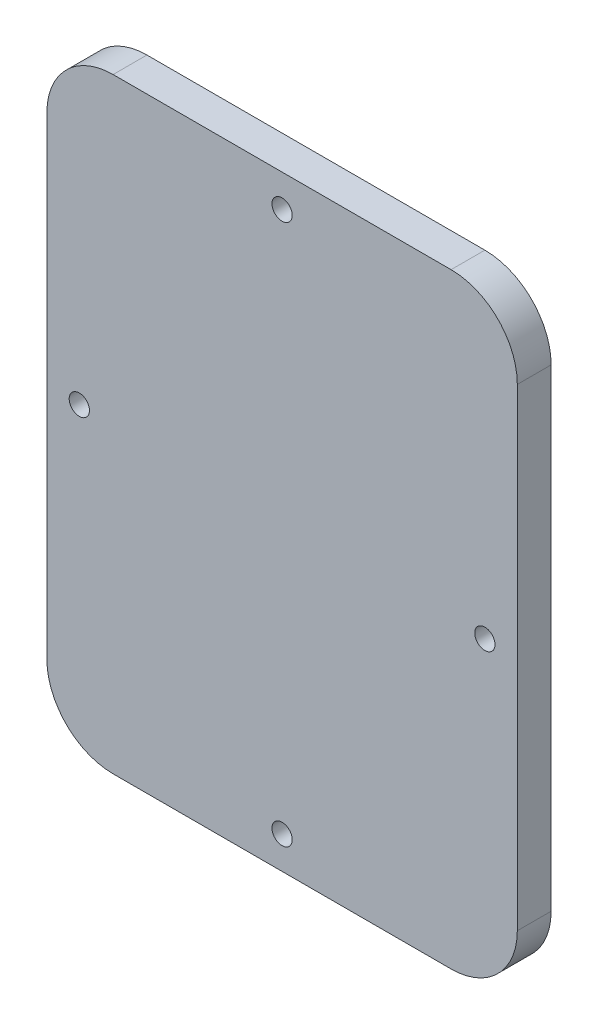
SolidWorks part; units mm, degrees
ref_plane "Plano frontal" through (0, 0, 0) normal (0, 0, 1) x (1, 0, 0)
ref_plane "Plano superior" through (0, 0, 0) normal (0, 1, 0) x (1, 0, 0)
ref_plane "Plano direito" through (0, 0, 0) normal (1, 0, 0) x (0, 0, -1)
sketch "Esboço1" plane through (0, 0, 0) normal (0, 0, 1) x (1, 0, 0)
  line L0 (25, 44.8) -> (-25, 44.8)
  line L1 (25, -45) -> (-25, -45)
  line L2 (35, -35) -> (35, 35)
  line L3 (25, 45) -> (-25, 45)
  line L4 (-35, -35) -> (-35, 35)
  line L5 (35, -45) -> (-35, 45) construction
  line L6 (35, 45) -> (-35, -45) construction
  line L7 (-34.8, -35) -> (-34.8, 35)
  line L8 (25, -44.8) -> (-25, -44.8)
  line L9 (34.8, -35) -> (34.8, 35)
  line L10 (0, 0) -> (0, 40) construction
  line L11 (0, 0) -> (-30, 0) construction
  arc A0 (-25, -45) -> (-35, -35) centre (-25, -35) cw
  arc A1 (25, -45) -> (35, -35) centre (25, -35) ccw
  arc A2 (35, 35) -> (25, 45) centre (25, 35) ccw
  arc A3 (-25, 45) -> (-35, 35) centre (-25, 35) ccw
  arc A4 (-25, 44.8) -> (-34.8, 35) centre (-25, 35) ccw
  arc A5 (-25, -44.8) -> (-34.8, -35) centre (-25, -35) cw
  arc A6 (25, -44.8) -> (34.8, -35) centre (25, -35) ccw
  arc A7 (34.8, 35) -> (25, 44.8) centre (25, 35) ccw
  circle A8 centre (0, 40) radius 1.5
  circle A9 centre (-30, 0) radius 1.5
  circle A10 centre (30, 0) radius 1.5
  circle A11 centre (0, -40) radius 1.5
  point P0 (0, 0)
  dimension "D3" = 10
  dimension "D7" = 3
  dimension "D8" = 3
  dimension "D1" = 90
  dimension "D2" = 70
  dimension "D5" = 40
  dimension "D6" = 30
  dimension "D4" = 0.2
extrude "Ressalto-extrusão1" add sketch "Esboço1" along normal blind 5 contours L9 A7 L0 A4 L7 A5 L8 A6 A10 A9 A8 A11
